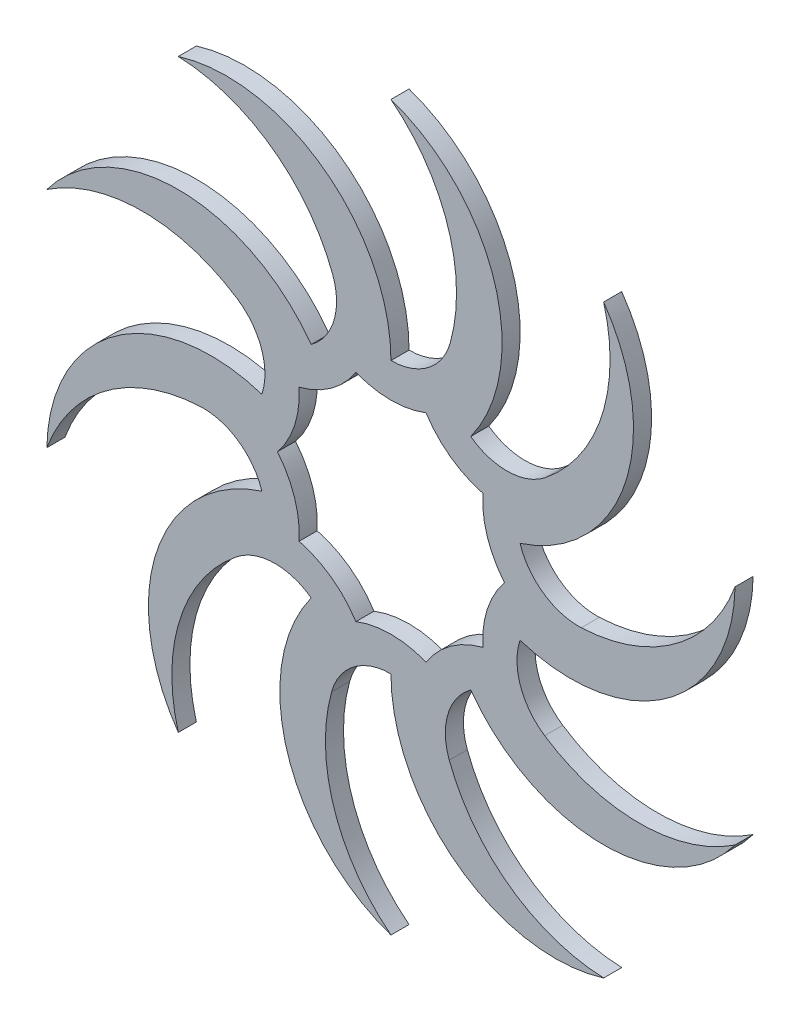
SolidWorks part; units mm, degrees
ref_plane "Front Plane" through (0, 0, 0) normal (0, 0, 1) x (1, 0, 0)
ref_plane "Top Plane" through (0, 0, 0) normal (0, 1, 0) x (1, 0, 0)
ref_plane "Right Plane" through (0, 0, 0) normal (1, 0, 0) x (0, 0, -1)
sketch "Sketch1" plane through (0, 0, 0) normal (0, 0, 1) x (1, 0, 0)
  line L0 (0, 0) -> (0, 50.8) construction
  line L1 (0, 0) -> (29.8595, 41.0981) construction
  line L2 (0, 0) -> (11.1973, 15.4118)
  line L3 (0, 0) -> (0, 19.05)
  circle A0 centre (0, 0) radius 50.8 construction
  arc A1 (11.1973, 15.4118) -> (0, 50.8) centre (-7.4666, 28.9719) ccw
  circle A2 centre (0, 0) radius 19.05 construction
  arc A3 (0, 19.05) -> (8.3348, 25.3972) centre (0, 27.696) ccw
  arc A4 (0, 50.8) -> (8.3348, 25.3972) centre (-14.9611, 31.8224) cw
  dimension "D2" = 101.6
  dimension "D3" = 38.1
  dimension "D1" = 36
extrude "Boss-Extrude1" add sketch "Sketch1" along normal blind 2.54
pattern_circular "CirPattern1" count 10 over 360 about axis through (0, 0, 0) along (0, 0, 1) of bodies 101
combine bodies "Combine1" bodies to combine 103 108 104 109 105 101 110 106 102 107
sketch "Sketch2" plane through (0, 0, 2.54) normal (0, 0, 1) x (1, 0, 0)
  arc A60 (12.8927, 9.3671) -> (15.9363, 0) centre (26.3405, 8.5585) ccw
  arc A62 (4.9246, 15.1563) -> (12.8927, 9.3671) centre (16.2793, 22.4065) ccw
  arc A64 (-4.9246, 15.1563) -> (4.9246, 15.1563) centre (0, 27.696) ccw
  arc A66 (-12.8927, 9.3671) -> (-4.9246, 15.1563) centre (-16.2793, 22.4065) ccw
  arc A68 (-15.9363, 0) -> (-12.8927, 9.3671) centre (-26.3405, 8.5585) ccw
  arc A70 (-12.8927, -9.3671) -> (-15.9363, 0) centre (-26.3405, -8.5585) ccw
  arc A72 (-4.9246, -15.1563) -> (-12.8927, -9.3671) centre (-16.2793, -22.4065) ccw
  arc A74 (4.9246, -15.1563) -> (-4.9246, -15.1563) centre (0, -27.696) ccw
  arc A76 (12.8927, -9.3671) -> (4.9246, -15.1563) centre (16.2793, -22.4065) ccw
  arc A78 (15.9363, 0) -> (12.8927, -9.3671) centre (26.3405, -8.5585) ccw
  arc A80 (12.8927, 9.3671) -> (15.9363, 0) centre (26.3405, 8.5585) ccw
  arc A82 (4.9246, 15.1563) -> (12.8927, 9.3671) centre (16.2793, 22.4065) ccw
  arc A84 (-4.9246, 15.1563) -> (4.9246, 15.1563) centre (0, 27.696) ccw
  arc A86 (-12.8927, 9.3671) -> (-4.9246, 15.1563) centre (-16.2793, 22.4065) ccw
  arc A88 (-15.9363, 0) -> (-12.8927, 9.3671) centre (-26.3405, 8.5585) ccw
  arc A90 (-12.8927, -9.3671) -> (-15.9363, 0) centre (-26.3405, -8.5585) ccw
  arc A92 (-4.9246, -15.1563) -> (-12.8927, -9.3671) centre (-16.2793, -22.4065) ccw
  arc A94 (4.9246, -15.1563) -> (-4.9246, -15.1563) centre (0, -27.696) ccw
  arc A96 (12.8927, -9.3671) -> (4.9246, -15.1563) centre (16.2793, -22.4065) ccw
  arc A98 (15.9363, 0) -> (12.8927, -9.3671) centre (26.3405, -8.5585) ccw
  dimension "D1" = 4.826
extrude "Cut-Extrude1" cut sketch "Sketch2" against normal up to next
